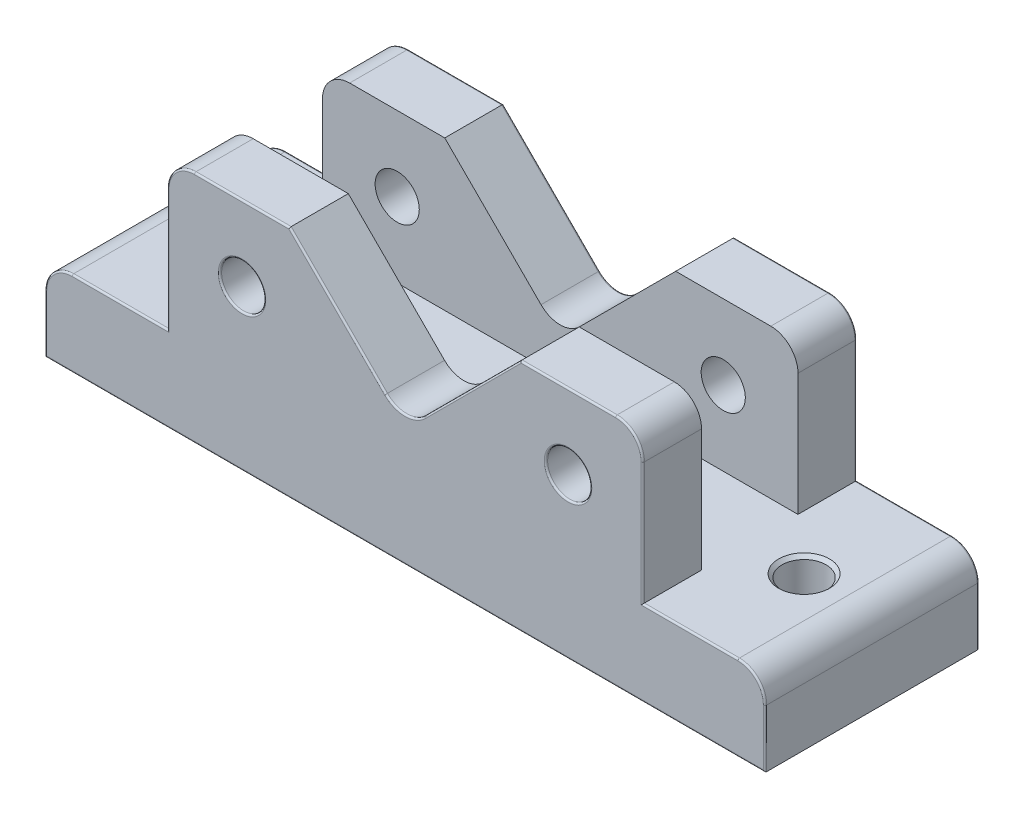
SolidWorks part; units mm, degrees
ref_plane "Front Plane" through (0, 0, 0) normal (0, 0, 1) x (1, 0, 0)
ref_plane "Top Plane" through (0, 0, 0) normal (0, 1, 0) x (1, 0, 0)
ref_plane "Right Plane" through (0, 0, 0) normal (1, 0, 0) x (0, 0, -1)
sketch "Sketch1" plane through (0, 0, 0) normal (0, 0, 1) x (1, 0, 0)
  line L0 (0, 0) -> (0, 100.1183) construction
  line L1 (0, 0) -> (106, 0) construction
  line L2 (0, 0) -> (0, 17)
  line L3 (8, 25) -> (36, 25)
  line L4 (36, 25) -> (36, 61)
  line L5 (44, 69) -> (72, 69)
  line L6 (72, 69) -> (100.3431, 40.6569)
  line L7 (106, 0) -> (106, 100.1183) construction
  line L8 (212, 0) -> (212, 100.1183) construction
  line L9 (140, 69) -> (111.6569, 40.6569)
  line L10 (168, 69) -> (140, 69)
  line L11 (176, 25) -> (176, 61)
  line L12 (204, 25) -> (176, 25)
  line L13 (212, 0) -> (212, 17)
  line L14 (0, 0) -> (212, 0)
  arc A0 (36, 61) -> (44, 69) centre (44, 61) cw
  arc A1 (0, 17) -> (8, 25) centre (8, 17) cw
  arc A2 (212, 17) -> (204, 25) centre (204, 17) ccw
  arc A3 (176, 61) -> (168, 69) centre (168, 61) ccw
  arc A4 (100.3431, 40.6569) -> (111.6569, 40.6569) centre (106, 46.3137) ccw
  point P11 (36, 69)
  point P14 (0, 25)
  point P27 (212, 25)
  point P28 (176, 69)
  point P31 (106, 35)
  dimension "D7" = 8
  dimension "D8" = 8
  dimension "D1" = 25
  dimension "D2" = 36
  dimension "D3" = 44
  dimension "D4" = 36
  dimension "D5" = 34
  dimension "D6" = 45
extrude "Boss-Extrude1" add sketch "Sketch1" along normal mid plane 63
sketch "Sketch2" plane through (176, 0, 0) normal (1, 0, 0) x (0, 0, -1)
  line L0 (-31.5, 25) -> (31.5, 25) construction
  line L1 (-14.2, 69.1058) -> (14.2, 69.1058)
  line L2 (-14.2, 69.1058) -> (-14.2, 25)
  line L3 (-14.2, 25) -> (14.2, 25)
  line L4 (14.2, 69.1058) -> (14.2, 25)
  line L5 (-14.2, 69.1058) -> (14.2, 25) construction
  line L6 (-14.2, 25) -> (14.2, 69.1058) construction
  line L7 (0, 0) -> (0, 47.0529) construction
  point P0 (0, 47.0529)
  point P9 (0, 0)
  point P11 (0, 0)
  point P12 (0, 0)
  dimension "D1" = 28.4
extrude "Cut-Extrude2" cut sketch "Sketch2" against normal through all
sketch "Sketch4" plane through (0, 0, 31.5) normal (0, 0, 1) x (1, 0, 0)
  line L0 (106, 0) -> (106, 95.4864) construction
  line L1 (0, 0) -> (212, 0) construction
  line L2 (72, 69) -> (44, 69) construction
  circle A0 centre (58, 47) radius 6.5
  circle A1 centre (154, 47) radius 6.5
  point P8 (54.2228, 54.6962)
  point P9 (0, 0)
  dimension "D1" = 13
  dimension "D2" = 48
  dimension "D3" = 22
extrude "Cut-Extrude3" cut sketch "Sketch4" against normal through all contours A1 | A0
sketch "Sketch5" plane through (0, 25, 0) normal (0, 1, 0) x (1, 0, 0)
  line L0 (0, 0) -> (212, 0) construction
  line L1 (212, -31.5) -> (212, 31.5) construction
  line L2 (0, -31.5) -> (0, 31.5) construction
  circle A0 centre (20, 0) radius 6.5
  circle A1 centre (192, 0) radius 6.5
  dimension "D1" = 13
  dimension "D2" = 20
  dimension "D3" = 20
extrude "Cut-Extrude4" cut sketch "Sketch5" against normal blind 63
fillet "Fillet1" radius 0.5 36 edges at (147.5, 47, 31.5) (64.5, 47, 31.5) (0, 8.5, 31.5) (2.3431, 22.6569, 31.5) (22, 25, 31.5) (36, 43, 31.5) (38.3431, 66.6569, 31.5) (58, 69, 31.5) (86.1716, 54.8284, 31.5) (106, 38.3137, 31.5) (125.8284, 54.8284, 31.5) (154, 69, 31.5) (173.6569, 66.6569, 31.5) (176, 43, 31.5) (190, 25, 31.5) (209.6569, 22.6569, 31.5) (212, 8.5, 31.5) (106, 0, 31.5) (147.5, 47, -31.5) (212, 8.5, -31.5) (209.6569, 22.6569, -31.5) (190, 25, -31.5) (176, 43, -31.5) (173.6569, 66.6569, -31.5) (154, 69, -31.5) (125.8284, 54.8284, -31.5) (106, 38.3137, -31.5) (86.1716, 54.8284, -31.5) (58, 69, -31.5) (38.3431, 66.6569, -31.5) (36, 43, -31.5) (22, 25, -31.5) (2.3431, 22.6569, -31.5) (0, 8.5, -31.5) (106, 0, -31.5) (64.5, 47, -31.5)
chamfer "Chamfer1" distance 1 angle 45 4 edges at (13.5, 0, 0) (20, 25, 6.5) (185.5, 0, 0) (192, 25, 6.5)
